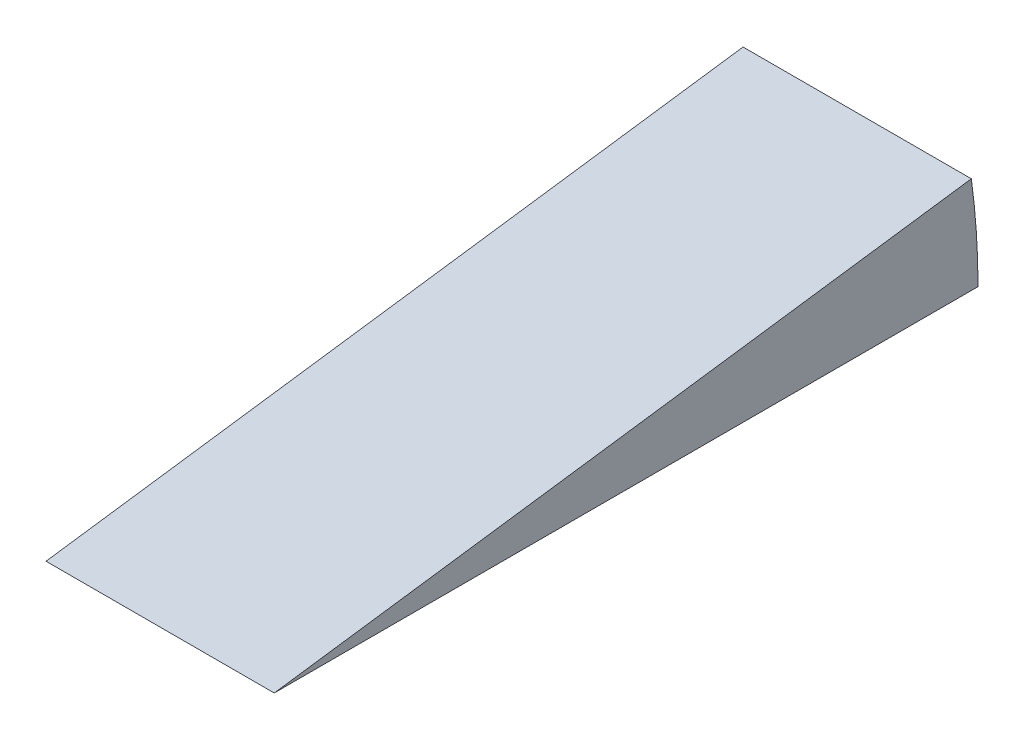
SolidWorks part; units mm, degrees
ref_plane "Alzado" through (0, 0, 0) normal (0, 0, 1) x (1, 0, 0)
ref_plane "Planta" through (0, 0, 0) normal (0, 1, 0) x (1, 0, 0)
ref_plane "Vista lateral" through (0, 0, 0) normal (1, 0, 0) x (0, 0, -1)
sketch "Croquis1" plane through (0, 0, 0) normal (0, 1, 0) x (1, 0, 0)
  line L1 (0, 0) -> (24, 0)
  line L2 (0, 0) -> (0, 144)
  line L3 (0, 144) -> (24, 144)
  line L4 (24, 0) -> (24, 144)
  dimension "D1" = 144
  dimension "D2" = 24
extrude "Saliente-Extruir1" add sketch "Croquis1" along normal blind 20
sketch "Croquis3" plane through (24, 0, 0) normal (1, 0, 0) x (0, 0, -1)
  line L0 (144, 20) -> (0, 0)
  line L1 (0, 0) -> (0, 20)
  line L2 (0, 20) -> (144, 20)
extrude "Cortar-Extruir2" cut sketch "Croquis3" against normal through all
sketch "Croquis4" plane through (0, 0, 0) normal (0, -1, 0) x (1, 0, 0)
  line L0 (24, 0) -> (24, -144) construction
  line L1 (24, -74) -> (0, -74)
  line L2 (24, -74) -> (24, -144)
  line L3 (24, -144) -> (0, -144)
  line L4 (0, -74) -> (0, -144)
  line L5 (0, 0) -> (24, 0) construction
  dimension "D1" = 74
revolve "Cortar-Revolución2" cut sketch "Croquis4" angle 360 about axis through (0, 0, 0) along (1, 0, 0)
